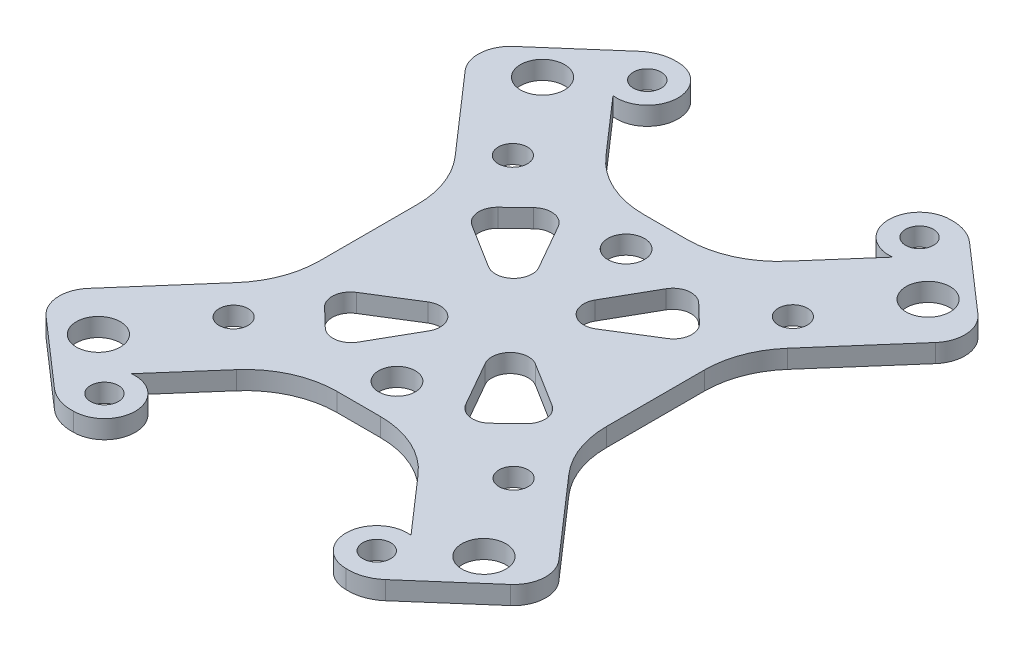
SolidWorks part; units mm, degrees
ref_plane "Alzado" through (0, 0, 0) normal (0, 0, 1) x (1, 0, 0)
ref_plane "Planta" through (0, 0, 0) normal (0, 1, 0) x (1, 0, 0)
ref_plane "Vista lateral" through (0, 0, 0) normal (1, 0, 0) x (0, 0, -1)
sketch "Croquis2" plane through (0, 0, 0) normal (0, 1, 0) x (1, 0, 0)
  line L0 (0, 0) -> (0, 10.4123) construction
  line L5 (0, 0) -> (3.0744, 0) construction
  line L7 (-18.1147, -11.9133) -> (-25.6658, -20.5534)
  line L14 (-15.6443, 5.3327) -> (-15.6443, -5.3327)
  line L15 (-2.3687, -16.7202) -> (2.3687, -16.7202)
  line L16 (15.6443, 5.3327) -> (15.6443, -5.3327)
  line L17 (-13.8775, 14.4472) -> (-9.9975, 10.4079) construction
  line L18 (-2.3687, 16.7202) -> (2.3687, 16.7202)
  line L19 (-9.8983, -20.1396) -> (-15.2581, -26.2722)
  line L20 (-25.3337, -25.492) -> (-21.87, -28.5191)
  line L21 (18.1147, -11.9133) -> (25.6658, -20.5534)
  line L22 (9.8983, -20.1396) -> (15.2581, -26.2722)
  line L23 (25.3337, -25.492) -> (21.87, -28.5191)
  line L24 (25.3337, 25.492) -> (21.87, 28.5191)
  line L25 (-9.8983, 20.1396) -> (-16.9315, 28.1869)
  line L26 (18.1147, 11.9133) -> (25.6658, 20.5534)
  line L27 (-25.3337, 25.492) -> (-21.87, 28.5191)
  line L30 (-18.1147, 11.9133) -> (-25.6658, 20.5534)
  line L32 (9.8983, 20.1396) -> (16.9315, 28.1869)
  line L34 (-21.87, -28.5191) -> (-18.0539, -31.8543)
  line L35 (21.87, 28.5191) -> (18.0539, 31.8543)
  line L37 (21.87, -28.5191) -> (18.0539, -31.8543)
  line L38 (-8.9971, 11.3688) -> (-10.9978, 9.447)
  line L39 (-10.671, 6.3078) -> (-5.8711, 3.3132)
  line L40 (-5.8736, 10.916) -> (-3.0744, 5.9996)
  line L41 (5.8736, 10.916) -> (3.0744, 5.9996)
  line L42 (10.671, 6.3078) -> (5.8711, 3.3132)
  line L43 (8.9971, 11.3688) -> (10.9978, 9.447)
  line L45 (8.9971, -11.3688) -> (10.9978, -9.447)
  line L46 (10.671, -6.3078) -> (5.8711, -3.3132)
  line L47 (5.8736, -10.916) -> (3.0744, -5.9996)
  line L48 (-5.8736, -10.916) -> (-3.0744, -5.9996)
  line L49 (-10.671, -6.3078) -> (-5.8711, -3.3132)
  line L50 (-8.9971, -11.3688) -> (-10.9978, -9.447)
  line L51 (-21.87, 28.5191) -> (-18.0539, 31.8543)
  arc A19 (-18.5328, -29.2275) -> (-21.87, -28.5191) centre (-19.5668, -25.8837) cw
  arc A20 (-25.3337, -25.492) -> (-25.6658, -20.5534) centre (-23.0305, -22.8566) cw
  arc A21 (25.3337, -25.492) -> (25.6658, -20.5534) centre (23.0305, -22.8566) ccw
  arc A22 (18.5328, -29.2275) -> (21.87, -28.5191) centre (19.5668, -25.8837) ccw
  arc A23 (19.9398, 29.3638) -> (21.87, 28.5191) centre (19.5668, 25.8837) cw
  arc A24 (25.3337, 25.492) -> (25.6658, 20.5534) centre (23.0305, 22.8566) cw
  arc A25 (-25.3337, 25.492) -> (-25.6658, 20.5534) centre (-23.0305, 22.8566) ccw
  arc A26 (-19.9398, 29.3638) -> (-21.87, 28.5191) centre (-19.5668, 25.8837) ccw
  circle A28 centre (21.1669, 24.2194) radius 2.4
  circle A41 centre (-14.85, -29.6034) radius 1.52
  arc A42 (-14.85, -32.9594) -> (-15.2581, -26.2722) centre (-14.85, -29.6034) ccw
  arc A43 (-18.0539, -31.8543) -> (-14.85, -32.9594) centre (-15.0926, -28.466) ccw
  arc A44 (18.0539, -31.8543) -> (14.85, -32.9594) centre (15.0926, -28.466) cw
  arc A45 (14.85, -32.9594) -> (15.2581, -26.2722) centre (14.85, -29.6034) cw
  circle A46 centre (14.85, -29.6034) radius 1.52
  arc A48 (9.8983, 20.1396) -> (2.3687, 16.7202) centre (2.3687, 26.7202) cw
  arc A50 (-3.0744, 5.9996) -> (-5.8711, 3.3132) centre (-4.8125, 5.01) cw
  arc A51 (-8.9971, 11.3688) -> (-5.8736, 10.916) centre (-7.6116, 9.9264) cw
  arc A52 (-10.9978, 9.447) -> (-10.671, 6.3078) centre (-9.6123, 8.0046) ccw
  arc A53 (10.9978, 9.447) -> (10.671, 6.3078) centre (9.6123, 8.0046) cw
  arc A54 (8.9971, 11.3688) -> (5.8736, 10.916) centre (7.6116, 9.9264) ccw
  arc A55 (3.0744, 5.9996) -> (5.8711, 3.3132) centre (4.8125, 5.01) ccw
  arc A56 (8.9971, -11.3688) -> (5.8736, -10.916) centre (7.6116, -9.9264) cw
  arc A57 (-8.9971, -11.3688) -> (-5.8736, -10.916) centre (-7.6116, -9.9264) ccw
  arc A58 (3.0744, -5.9996) -> (5.8711, -3.3132) centre (4.8125, -5.01) cw
  arc A59 (10.9978, -9.447) -> (10.671, -6.3078) centre (9.6123, -8.0046) ccw
  arc A60 (-10.9978, -9.447) -> (-10.671, -6.3078) centre (-9.6123, -8.0046) cw
  arc A61 (-3.0744, -5.9996) -> (-5.8711, -3.3132) centre (-4.8125, -5.01) ccw
  circle A62 centre (-0.05, 12.4971) radius 2
  circle A63 centre (-0.05, -12.4971) radius 2
  arc A64 (-18.1147, 11.9133) -> (-15.6443, 5.3327) centre (-25.6443, 5.3327) cw
  arc A65 (-15.6443, -5.3327) -> (-18.1147, -11.9133) centre (-25.6443, -5.3327) cw
  arc A66 (-2.3687, -16.7202) -> (-9.8983, -20.1396) centre (-2.3687, -26.7202) ccw
  arc A67 (2.3687, -16.7202) -> (9.8983, -20.1396) centre (2.3687, -26.7202) cw
  arc A68 (15.6443, -5.3327) -> (18.1147, -11.9133) centre (25.6443, -5.3327) ccw
  arc A69 (18.1147, 11.9133) -> (15.6443, 5.3327) centre (25.6443, 5.3327) ccw
  arc A70 (14.85, 32.9594) -> (15.2581, 26.2722) centre (14.85, 29.6034) ccw
  arc A71 (-9.8983, 20.1396) -> (-2.3687, 16.7202) centre (-2.3687, 26.7202) ccw
  arc A72 (18.0539, 31.8543) -> (14.85, 32.9594) centre (15.0926, 28.466) ccw
  arc A73 (-18.0539, 31.8543) -> (-14.85, 32.9594) centre (-15.0926, 28.466) cw
  circle A74 centre (-14.85, 29.6034) radius 1.52
  arc A75 (-14.85, 32.9594) -> (-15.2581, 26.2722) centre (-14.85, 29.6034) cw
  circle A76 centre (14.85, 29.6034) radius 1.52
  circle A77 centre (-15.0711, 15.1651) radius 1.59
  circle A81 centre (15.4289, 15.2056) radius 1.59
  circle A82 centre (15.4694, -15.2943) radius 1.59
  circle A85 centre (-15.0306, -15.3349) radius 1.59
  circle A86 centre (-20.7686, -24.3486) radius 2.4
  circle A87 centre (-20.8331, 24.1636) radius 2.4
  circle A88 centre (21.2313, -24.2929) radius 2.4
  point P22 (-19.2347, -30.8223)
  point P25 (-27.9691, -23.1888)
  point P34 (27.9691, -23.1888)
  point P35 (19.2347, -30.8223)
  point P53 (19.2347, 30.8223)
  point P54 (-27.9691, 23.1888)
  point P55 (-19.2347, 30.8223)
  point P89 (-9.9975, 10.4079)
  point P92 (0.8383, -0.8727)
  point P96 (-7.1445, 13.1483)
  point P99 (-12.8504, 7.6675)
  point P112 (12.8504, 7.6675)
  point P113 (7.1445, 13.1483)
  point P114 (9.9975, 10.4079)
  point P135 (9.9975, -10.4079)
  point P136 (12.8504, -7.6675)
  point P137 (-12.8504, -7.6675)
  point P138 (-9.9975, -10.4079)
  point P143 (-15.6443, 9.0867)
  point P146 (-15.6443, -9.0867)
  point P149 (-6.9099, -16.7202)
  point P152 (6.9099, -16.7202)
  point P155 (15.6443, -9.0867)
  point P158 (15.6443, 9.0867)
  dimension "D3" = 3.5
  dimension "D5" = 4.8
  dimension "D2" = 3.18
  dimension "D9" = 13.8199
  dimension "D7" = 4.8
  dimension "D10" = 4.5
  dimension "D12" = 10
  dimension "D8" = 2
  dimension "D11" = 4
  dimension "D4" = 4.8
  dimension "D6" = 4.8
  dimension "D14" = 29.7
  dimension "D15" = 14.8
sketch "Croquis3" plane through (0, 0, 0) normal (0, 1, 0) x (1, 0, 0)
  line L0 (0, 0) -> (0, 33.3632) construction
extrude "Saliente-Extruir1" add sketch "Croquis2" along normal blind 2
